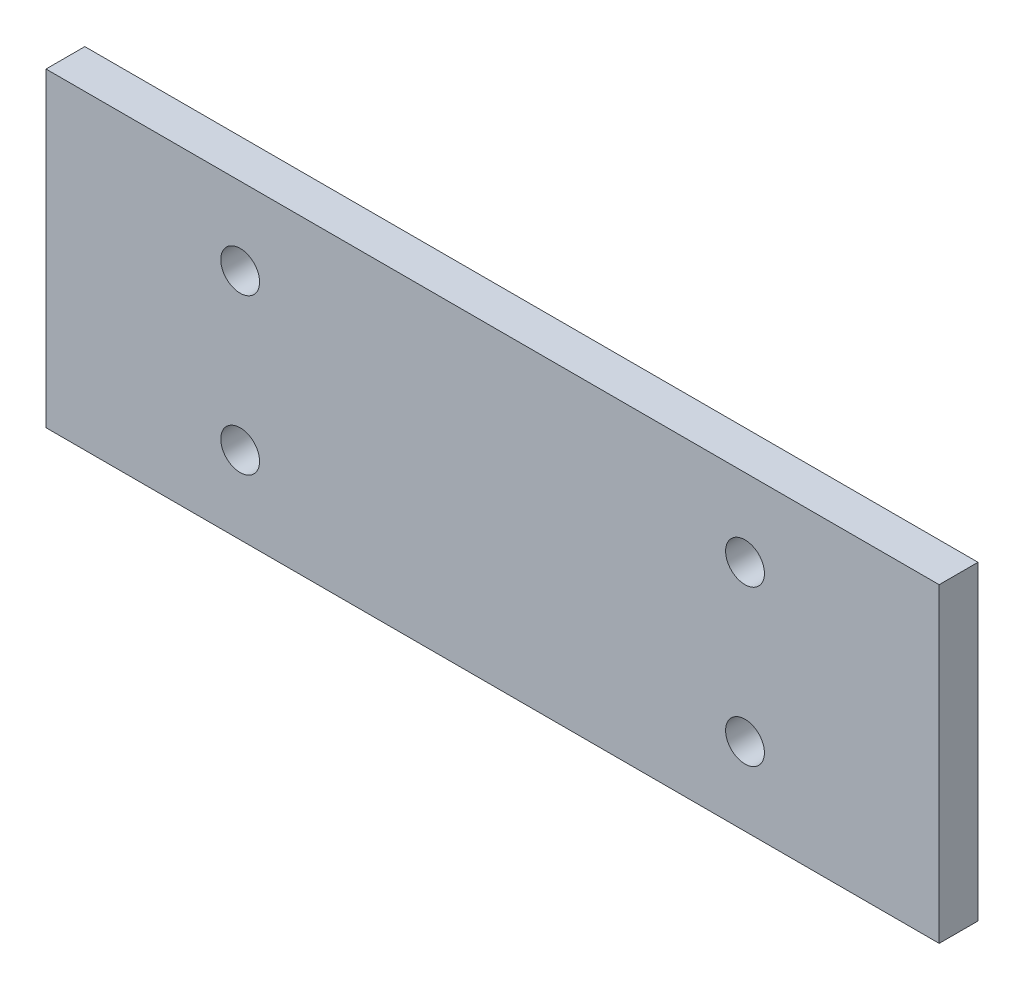
SolidWorks part; units mm, degrees
ref_plane "Front Plane" through (0, 0, 0) normal (0, 0, 1) x (1, 0, 0)
ref_plane "Top Plane" through (0, 0, 0) normal (0, 1, 0) x (1, 0, 0)
ref_plane "Right Plane" through (0, 0, 0) normal (1, 0, 0) x (0, 0, -1)
sketch "Sketch1" plane through (0, 0, 0) normal (0, 0, 1) x (1, 0, 0)
  line L0 (-57.5, 0) -> (57.5, 0)
  line L1 (-57.5, 0) -> (-57.5, 40)
  line L2 (-57.5, 40) -> (57.5, 40)
  line L3 (57.5, 40) -> (57.5, 0)
  circle A0 centre (-32.5, 30) radius 2.5
  circle A1 centre (-32.5, 10) radius 2.5
  circle A2 centre (32.5, 10) radius 2.5
  circle A3 centre (32.5, 30) radius 2.5
  point P4 (0, 0)
  point P6 (0, 0)
  dimension "D1" = 2.5
  dimension "D2" = 115
  dimension "D3" = 40
  dimension "D4" = 65
extrude "Boss-Extrude1" add sketch "Sketch1" along normal blind 5
